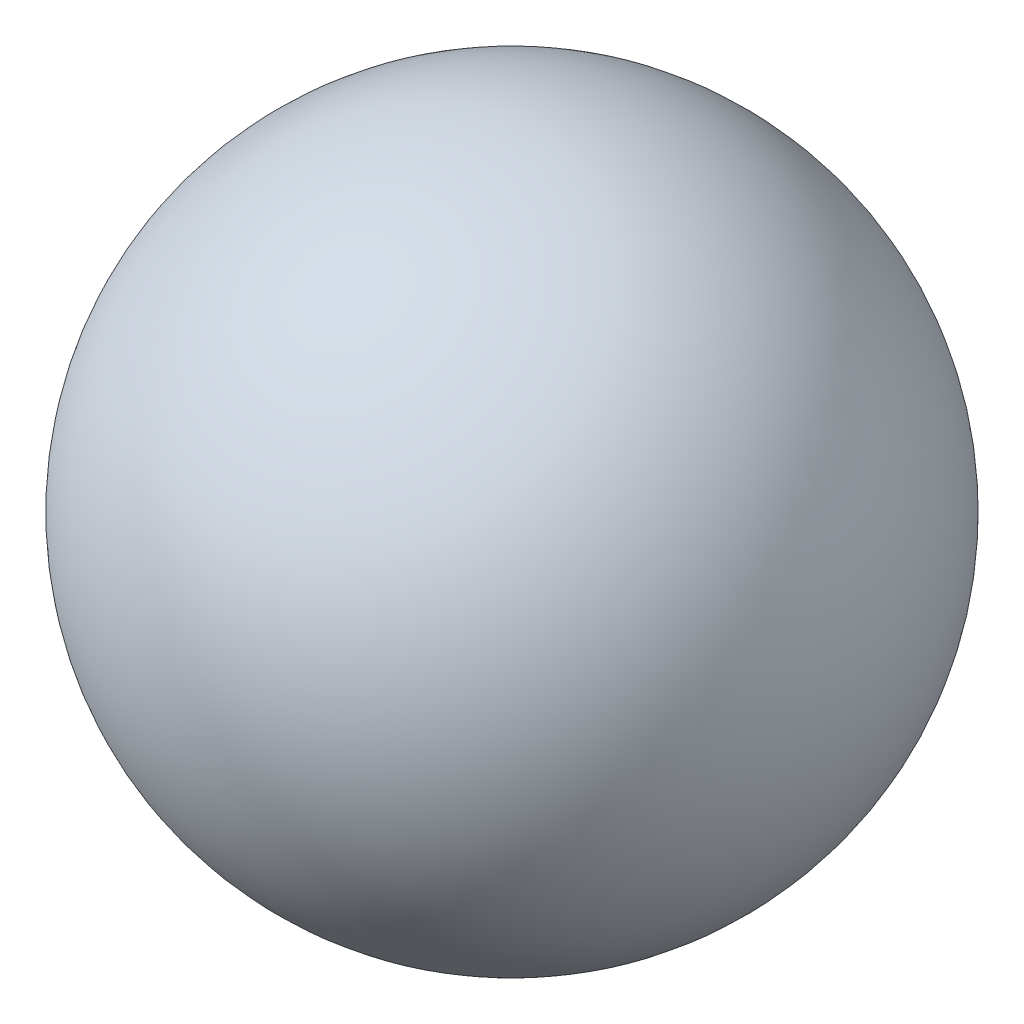
SolidWorks part; units mm, degrees
ref_plane "Спереди" through (0, 0, 0) normal (0, 0, 1) x (1, 0, 0)
ref_plane "Сверху" through (0, 0, 0) normal (0, 1, 0) x (1, 0, 0)
ref_plane "Справа" through (0, 0, 0) normal (1, 0, 0) x (0, 0, -1)
other "Configuration Table"
sketch "Эскиз1" plane through (0, 0, 0) normal (0, 0, 1) x (1, 0, 0)
  line L0 (0, 0) -> (0, 30)
  line L1 (0, -30) -> (0, 0)
  arc A0 (0, 30) -> (0, -30) centre (0, 0) cw
  dimension "D1" = 30
revolve "Повернуть1" add sketch "Эскиз1" angle 360 about L0
